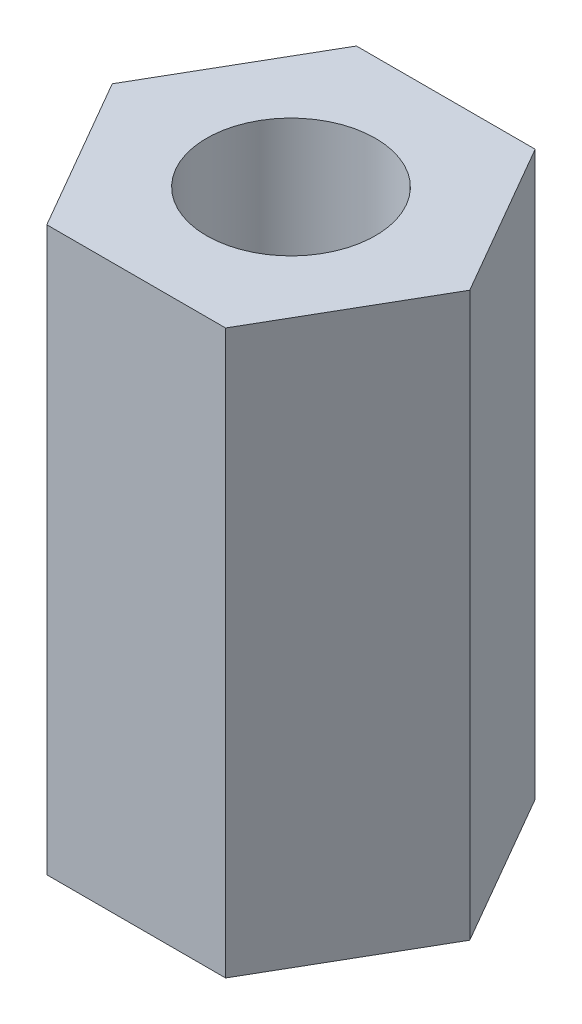
SolidWorks part; units mm, degrees
ref_plane "前视基准面" through (0, 0, 0) normal (0, 0, 1) x (1, 0, 0)
ref_plane "上视基准面" through (0, 0, 0) normal (0, 1, 0) x (1, 0, 0)
ref_plane "右视基准面" through (0, 0, 0) normal (1, 0, 0) x (0, 0, -1)
sketch "草图1" plane through (0, 0, 0) normal (0, 1, 0) x (1, 0, 0)
  line L1 (2.8554, 0) -> (1.2677, 2.75)
  line L2 (1.2677, 2.75) -> (-1.9077, 2.75)
  line L3 (-1.9077, 2.75) -> (-3.4954, 0)
  line L4 (-3.4954, 0) -> (-1.9077, -2.75)
  line L5 (-1.9077, -2.75) -> (1.2677, -2.75)
  line L6 (1.2677, -2.75) -> (2.8554, 0)
  circle A0 centre (-0.32, 0) radius 2.75 construction
  circle A1 centre (-0.32, 0) radius 1.5
  dimension "D1" = 5.5
  dimension "D2" = 3
extrude "凸台-拉伸1" add sketch "草图1" along normal blind 10
